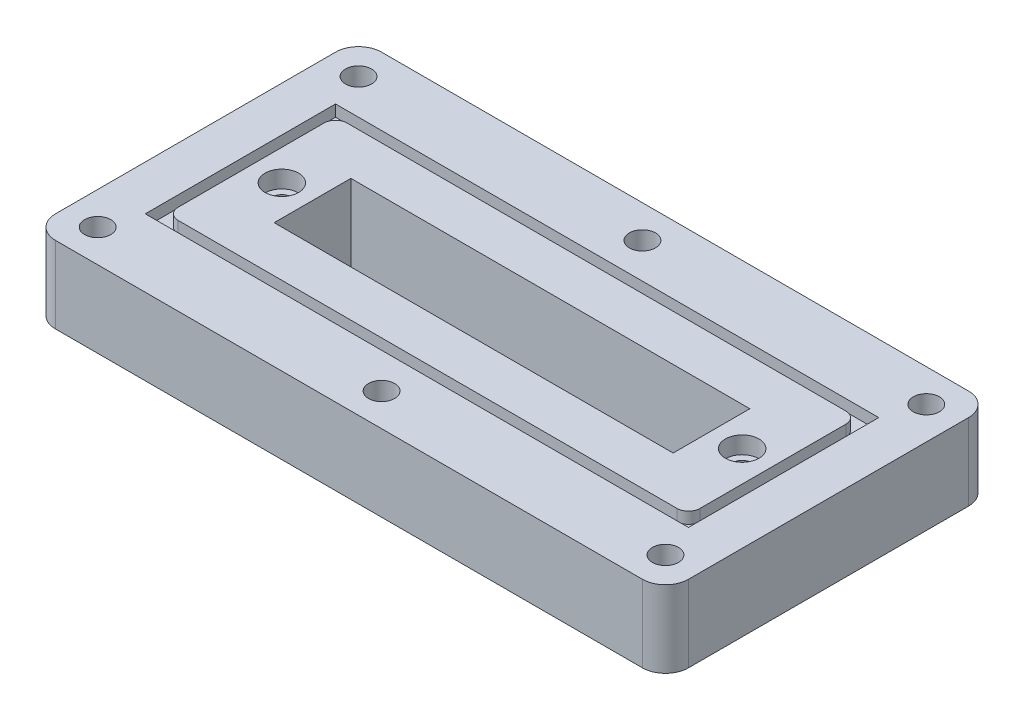
SolidWorks part; units mm, degrees
ref_plane "Front Plane" through (0, 0, 0) normal (0, 0, 1) x (1, 0, 0)
ref_plane "Top Plane" through (0, 0, 0) normal (0, 1, 0) x (1, 0, 0)
ref_plane "Right Plane" through (0, 0, 0) normal (1, 0, 0) x (0, 0, -1)
sketch "Sketch1" plane through (0, 0, 0) normal (0, 1, 0) x (1, 0, 0)
  line L1 (-52.3875, -26.9875) -> (52.3875, -26.9875)
  line L2 (-52.3875, -26.9875) -> (-52.3875, 26.9875)
  line L3 (-52.3875, 26.9875) -> (52.3875, 26.9875)
  line L4 (52.3875, -26.9875) -> (52.3875, 26.9875)
  line L5 (-52.3875, -26.9875) -> (52.3875, 26.9875) construction
  line L6 (-52.3875, 26.9875) -> (52.3875, -26.9875) construction
  point P0 (0, 0)
  dimension "D1" = 104.775
  dimension "D2" = 53.975
extrude "Boss-Extrude1" add sketch "Sketch1" along normal blind 12.7
sketch "Sketch3" plane through (0, 12.7, 0) normal (0, 1, 0) x (1, 0, 0)
  line L1 (-43.18, -13.97) -> (43.18, -13.97)
  line L2 (-43.18, -13.97) -> (-43.18, 13.97)
  line L3 (-43.18, 13.97) -> (43.18, 13.97)
  line L4 (43.18, -13.97) -> (43.18, 13.97)
  line L5 (-43.18, -13.97) -> (43.18, 13.97) construction
  line L6 (-43.18, 13.97) -> (43.18, -13.97) construction
  line L14 (-44.958, 15.748) -> (44.958, 15.748)
  line L15 (44.958, -15.748) -> (44.958, 15.748)
  line L16 (-44.958, -15.748) -> (44.958, -15.748)
  line L17 (-44.958, -15.748) -> (-44.958, 15.748)
  point P0 (0, 0)
  point P6 (0, 0)
  dimension "D1" = 27.94
  dimension "D2" = 86.36
  dimension "D3" = 1.778
extrude "Cut-Extrude1" cut sketch "Sketch3" against normal blind 1.905
fillet "Fillet1" radius 1.905 4 edges at (43.18, 11.7475, 13.97) (43.18, 11.7475, -13.97) (-43.18, 11.7475, 13.97) (-43.18, 11.7475, -13.97)
sketch "Sketch4" plane through (0, 0, 0) normal (0, -1, 0) x (1, 0, 0)
  line L0 (46.99, 21.59) -> (52.3875, 21.59) construction
  line L1 (-52.3875, -26.9875) -> (-52.3875, 26.9875) construction
  line L3 (52.3875, 26.9875) -> (52.3875, -26.9875) construction
  line L6 (-46.99, 21.59) -> (-52.3875, 21.59) construction
  line L7 (-46.99, 21.59) -> (-46.99, 26.9875) construction
  line L8 (-52.3875, 26.9875) -> (52.3875, 26.9875) construction
  line L9 (-46.99, -21.59) -> (-46.99, -26.9875) construction
  line L11 (52.3875, -26.9875) -> (-52.3875, -26.9875) construction
  line L12 (0, -26.9875) -> (0, 26.9875) construction
  circle A0 centre (-46.99, 21.59) radius 2.159
  circle A1 centre (46.99, 21.59) radius 2.159
  circle A2 centre (-46.99, -21.59) radius 2.159
  circle A3 centre (46.99, -21.59) radius 2.159
  circle A4 centre (0, 21.59) radius 2.159
  circle A5 centre (0, -21.59) radius 2.159
  point P22 (-46.99, -21.59)
  dimension "D3" = 4.318
  dimension "D4" = 4.318
  dimension "D5" = 4.318
  dimension "D6" = 4.318
  dimension "D7" = 4.318
  dimension "D8" = 4.318
  dimension "D1" = 93.98
  dimension "D2" = 43.18
extrude "Cut-Extrude2" cut sketch "Sketch4" against normal through all
sketch "Sketch8" plane through (0, 0, 0) normal (0, -1, 0) x (1, 0, 0)
  circle A0 centre (-46.99, 21.59) radius 3.6195
  circle A1 centre (0, 21.59) radius 3.6195
  circle A2 centre (46.99, 21.59) radius 3.6195
  circle A3 centre (46.99, -21.59) radius 3.6195
  circle A4 centre (0, -21.59) radius 3.6195
  circle A5 centre (-46.99, -21.59) radius 3.6195
  dimension "D1" = 7.239
  dimension "D2" = 7.239
  dimension "D3" = 7.239
  dimension "D4" = 7.239
  dimension "D5" = 7.239
  dimension "D6" = 7.239
extrude "Cut-Extrude3" cut sketch "Sketch8" against normal blind 4.572
fillet "Fillet2" radius 3.81 4 edges at (-52.3875, 6.35, 26.9875) (-52.3875, 6.35, -26.9875) (52.3875, 6.35, 26.9875) (52.3875, 6.35, -26.9875)
sketch "Sketch13" plane through (0, 0, 0) normal (0, -1, 0) x (1, 0, 0)
  line L1 (-33.02, -6.35) -> (33.02, -6.35)
  line L2 (-33.02, -6.35) -> (-33.02, 6.35)
  line L3 (-33.02, 6.35) -> (33.02, 6.35)
  line L4 (33.02, -6.35) -> (33.02, 6.35)
  line L5 (-33.02, -6.35) -> (33.02, 6.35) construction
  line L6 (-33.02, 6.35) -> (33.02, -6.35) construction
  point P0 (0, 0)
  dimension "D1" = 66.04
  dimension "D2" = 12.7
extrude "Cut-Extrude4" cut sketch "Sketch13" against normal through all contours L1 L4 L3 L2
sketch "Sketch15" [suppressed] plane through (0, 12.7, 0) normal (0, 1, 0) x (1, 0, 0)
  line L1 (-36.195, -9.7155) -> (36.195, -9.7155)
  line L2 (-36.195, -9.7155) -> (-36.195, 9.7155)
  line L3 (-36.195, 9.7155) -> (36.195, 9.7155)
  line L4 (36.195, -9.7155) -> (36.195, 9.7155)
  line L5 (-36.195, -9.7155) -> (36.195, 9.7155) construction
  line L6 (-36.195, 9.7155) -> (36.195, -9.7155) construction
  point P0 (0, 0)
  dimension "D1" = 72.39
  dimension "D2" = 19.431
sketch "Sketch18" plane through (0, 12.7, 0) normal (0, 1, 0) x (1, 0, 0)
  line L0 (-38.1, 0) -> (38.1, 0) construction
  line L1 (0, 26.9875) -> (0, -26.9875) construction
  line L2 (48.5775, 26.9875) -> (-48.5775, 26.9875) construction
  line L3 (-48.5775, -26.9875) -> (48.5775, -26.9875) construction
  circle A0 centre (-38.1, 0) radius 1.4605
  circle A1 centre (38.1, 0) radius 1.4605
  point P10 (0, 0)
  point P11 (0, 0)
  dimension "D2" = 2.921
  dimension "D3" = 2.921
  dimension "D1" = 76.2
hole_wizard "CBORE for #4 Socket Head Cap Screw3" positions "Sketch25" profile "Sketch26" counterbore size "#4" standard "ANSI Inch" end condition through all
sketch "Sketch25" plane through (0, 12.7, 0) normal (0, 1, 0) x (1, 0, 0)
  point P0 (-38.1, 0)
  point P3 (38.1, 0)
sketch "Sketch26" plane through (-38.1, 12.7, 0) normal (1, 0, 0) x (0, 0, 1)
  line L0 (0, 0) -> (0, 12.7)
  line L1 (0, 12.7) -> (1.6319, 12.7)
  line L3 (1.6319, 12.7) -> (1.632, 2.8448)
  line L4 (1.632, 2.8448) -> (2.7788, 2.8448)
  line L5 (2.7788, 2.8448) -> (2.7788, 0)
  line L7 (2.7788, 0) -> (0, 0)
  line L11 (0, -6.35) -> (0, 107.95) construction
  dimension "Thru Hole Dia." = 3.2639
  dimension "Thru Hole Depth" = 12.7
  dimension "C'Bore Dia." = 5.5575
  dimension "C'Bore Depth" = 2.8448
